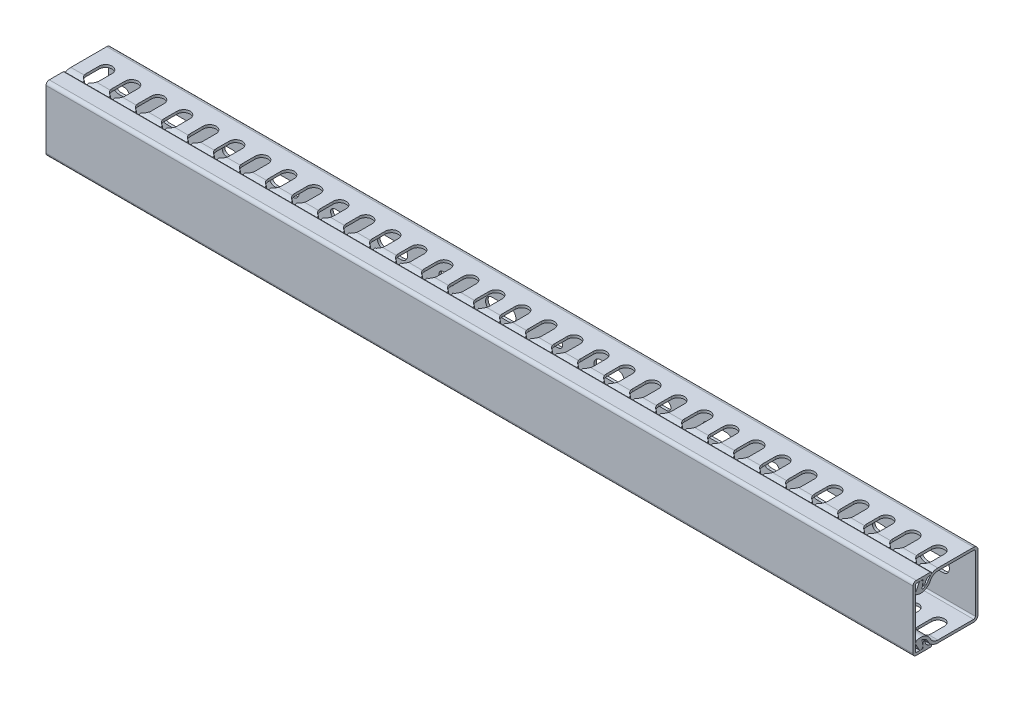
SolidWorks part; units mm, degrees
ref_plane "Front" through (0, 0, 0) normal (0, 0, 1) x (1, 0, 0)
ref_plane "Top" through (0, 0, 0) normal (0, 1, 0) x (1, 0, 0)
ref_plane "Right" through (0, 0, 0) normal (1, 0, 0) x (0, 0, -1)
sketch "Sketch1" plane through (0, 0, 0) normal (1, 0, 0) x (0, 0, -1)
  line L0 (-25.4152, -12.6264) -> (-25.8698, -10.0482)
  line L1 (0, -15) -> (-18.5359, -15)
  line L5 (-27.2927, -13.2506) -> (-28.6927, -10.4771)
  line L6 (-26.4732, -11) -> (-23.2292, -11) construction
  line L7 (0, 0) -> (-35.6549, 0) construction
  line L8 (0, 0) -> (0, -15)
  line L9 (-30, 0) -> (-30, -15)
  line L10 (-30, -15) -> (-22, -15)
  line L11 (-25.4, -11.5) -> (-25.4, -13.8)
  line L12 (-25.4, -13.8) -> (-28.8, -13.8)
  line L13 (-28.8, -13.8) -> (-28.8, 13.8)
  line L15 (-21.4, -11) -> (-21.4, -18.4358) construction
  line L16 (-1.2, 0) -> (-1.2, -13.8)
  line L17 (-1.2, -13.8) -> (-18.5359, -13.8)
  line L19 (-21.9633, -11.6409) -> (-23.6964, -8.021) construction
  line L20 (-28.8, -8.8) -> (-24.4003, -8.8) construction
  line L21 (-28.8, 8.8) -> (-24.4003, 8.8) construction
  line L22 (-21.4, 11) -> (-21.4, 18.4358) construction
  line L23 (-23.0457, -12.1591) -> (-24.7788, -8.5392) construction
  line L24 (-26.4732, 11) -> (-23.2292, 11) construction
  line L25 (-1.2, 13.8) -> (-18.5359, 13.8)
  line L26 (-1.2, 0) -> (-1.2, 13.8)
  line L27 (-25.4, 13.8) -> (-28.8, 13.8)
  line L28 (-25.4, 11.5) -> (-25.4, 13.8)
  line L29 (-30, 15) -> (-22, 15)
  line L30 (-30, 0) -> (-30, 15)
  line L31 (0, 0) -> (0, 15)
  line L32 (-27.2927, 13.2506) -> (-28.6927, 10.4771)
  line L33 (0, 15) -> (-18.5359, 15)
  line L34 (-25.4152, 12.6264) -> (-25.8698, 10.0482)
  arc A0 (-25.8698, -10.0482) -> (-23.0457, -12.1591) centre (-26.4732, -13.8) cw
  arc A1 (-22, -15) -> (-22, -13.8) centre (-22, -14.4) ccw
  arc A2 (-22, -13.8) -> (-24.4003, -11.4825) centre (-22, -11.3982) cw
  arc A3 (-24.4003, -11.4825) -> (-25.4, -11.5) centre (-24.9, -11.5) ccw
  arc A4 (-23.0457, -12.1591) -> (-18.5359, -15) centre (-18.5359, -10) ccw
  arc A5 (-25.4152, -12.6264) -> (-27.2927, -13.2506) centre (-26.4, -12.8) cw
  arc A6 (-21.9633, -11.6409) -> (-18.5359, -13.8) centre (-18.5359, -10) ccw
  arc A7 (-28.1317, -9.0831) -> (-21.9633, -11.6409) centre (-26.4732, -13.8) cw
  arc A8 (-25.6793, -8.8634) -> (-21.9633, -11.6409) centre (-26.4732, -13.8) cw construction
  arc A9 (-28.1317, -9.0831) -> (-28.6927, -10.4771) centre (-27.8, -10.0265) ccw
  arc A10 (-28.1317, 9.0831) -> (-28.6927, 10.4771) centre (-27.8, 10.0265) cw
  arc A11 (-28.1317, 9.0831) -> (-21.9633, 11.6409) centre (-26.4732, 13.8) ccw
  arc A12 (-21.9633, 11.6409) -> (-18.5359, 13.8) centre (-18.5359, 10) cw
  arc A13 (-25.4152, 12.6264) -> (-27.2927, 13.2506) centre (-26.4, 12.8) ccw
  arc A14 (-23.0457, 12.1591) -> (-18.5359, 15) centre (-18.5359, 10) cw
  arc A15 (-24.4003, 11.4825) -> (-25.4, 11.5) centre (-24.9, 11.5) cw
  arc A16 (-22, 13.8) -> (-24.4003, 11.4825) centre (-22, 11.3982) ccw
  arc A17 (-22, 15) -> (-22, 13.8) centre (-22, 14.4) cw
  arc A18 (-25.8698, 10.0482) -> (-23.0457, 12.1591) centre (-26.4732, 13.8) ccw
  point P31 (-20, -15)
  point P61 (-28.8, 0)
  point P62 (-20, 15)
  dimension "D2" = 20
  dimension "D6" = 1.2
  dimension "D8" = 0.6
  dimension "D11" = 0.5
  dimension "D4" = 1
  dimension "D5" = 5
  dimension "D13" = 5
  dimension "D15" = 5
  dimension "D16" = 1
  dimension "D1" = 30
  dimension "D7" = 1.2
  dimension "D9" = 3.4
  dimension "D10" = 1.2
  dimension "D12" = 4
  dimension "D17" = 10
  dimension "D18" = 4
  dimension "D3" = 30
  dimension "D14" = 1.2
extrude "Boss-Extrude1" add sketch "Sketch1" along normal blind 400 contours A18 L34 A13 L32 A10 A11 A12 L25 L26 L16 L17 A6 A7 A9 L5 A5 L0 A0 A4 L1 L8 L31 L33 A14 | A17 L29 L30 L9 L10 A1 A2 A3 L11 L12 L13 L27 L28 A15 A16
sketch "Sketch2" plane through (0, 0, 0) normal (0, 1, 0) x (1, 0, 0)
  line L0 (9, -11.5) -> (9, -17.5) construction
  line L1 (12, -11.5) -> (12, -17.5)
  line L2 (6, -11.5) -> (6, -17.5)
  line L3 (400, 0) -> (0, 0) construction
  line L5 (8, -20.3284) -> (8, -30.388)
  line L6 (8, -30.388) -> (10, -30.388)
  line L7 (10, -20.3284) -> (10, -30.388)
  line L8 (8, -20.3284) -> (10, -30.388) construction
  line L9 (8, -30.388) -> (10, -20.3284) construction
  line L10 (0, 0) -> (0, -18.5359) construction
  arc A0 (12, -11.5) -> (6, -11.5) centre (9, -11.5) ccw
  arc A1 (6, -17.5) -> (8, -20.3284) centre (9, -17.5) ccw
  arc A2 (10, -20.3284) -> (12, -17.5) centre (9, -17.5) ccw
  point P2 (10.517, -14.5)
  point P7 (9, -25.3582)
  dimension "D1" = 6
  dimension "D2" = 6
  dimension "D3" = 11.5
  dimension "D4" = 2
  dimension "D5" = 6
extrude "Cut-Extrude1" cut sketch "Sketch2" against normal through all both and the other way through all
sketch "Sketch4" plane through (0, 0, 0) normal (0, 0, 1) x (1, 0, 0)
  line L0 (0, 0) -> (400, 0) construction
  line L1 (400, -13.8) -> (400, 13.8) construction
  line L2 (4.5, 0) -> (7.5, 0) construction
  line L3 (4.5, 2) -> (7.5, 2)
  line L4 (4.5, -2) -> (7.5, -2)
  line L5 (27, 0) -> (35, 0) construction
  line L6 (27, 3) -> (35, 3)
  line L7 (27, -3) -> (35, -3)
  line L8 (0, -13.8) -> (0, 13.8) construction
  arc A0 (4.5, 2) -> (4.5, -2) centre (4.5, 0) ccw
  arc A1 (7.5, -2) -> (7.5, 2) centre (7.5, 0) ccw
  arc A2 (27, 3) -> (27, -3) centre (27, 0) ccw
  arc A3 (35, -3) -> (35, 3) centre (35, 0) ccw
  point P7 (6, 0)
  point P12 (31, 0)
  dimension "D1" = 6
  dimension "D2" = 8
  dimension "D3" = 3
  dimension "D4" = 4
  dimension "D5" = 25
  dimension "D6" = 6
extrude "Cut-Extrude3" cut sketch "Sketch4" along normal through all
pattern_linear "LPattern1" count 33 spacing 12 along (1, 0, 0) of "Cut-Extrude1"
pattern_linear "LPattern2" count 8 spacing 50 along (1, 0, 0) of "Cut-Extrude3"
fillet "Fillet1" radius 1.5 2 edges at (200, -15, 30) (200, 15, 30)
fillet "Fillet2" radius 2 2 edges at (200, -15, 0) (200, 15, 0)
fillet "Fillet3" radius 0.8 2 edges at (200, -13.8, 1.2) (200, 13.8, 1.2)
fillet "Fillet4" radius 0.3 2 edges at (200, -13.8, 28.8) (200, 13.8, 28.8)
equation "\"Length\"=400"
equation "\"Slot spacing\"= 12"
equation "\"D1@Boss-Extrude1\"=\"Length\""
equation "\"D3@LPattern1\"=\"Slot spacing\""
